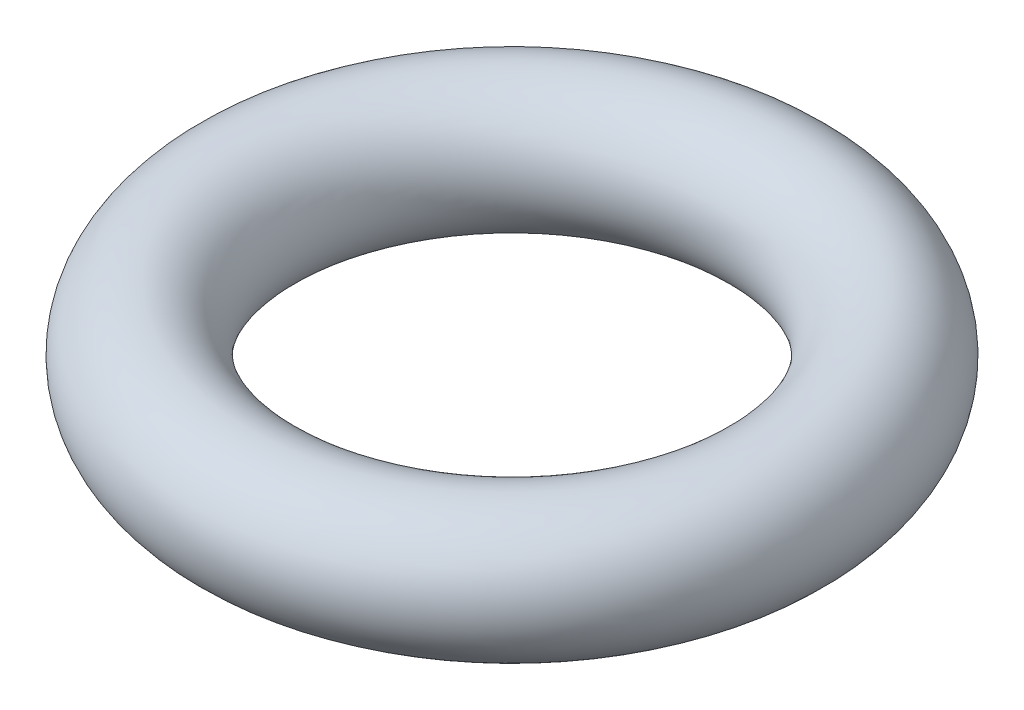
SolidWorks part; units mm, degrees
ref_plane "Front Plane" through (0, 0, 0) normal (0, 0, 1) x (1, 0, 0)
ref_plane "Top Plane" through (0, 0, 0) normal (0, 1, 0) x (1, 0, 0)
ref_plane "Right Plane" through (0, 0, 0) normal (1, 0, 0) x (0, 0, -1)
sketch "Sketch1" plane through (0, 0, 0) normal (0, 0, 1) x (1, 0, 0)
  line L0 (0, 0) -> (0, 24.0291) construction
  circle A0 centre (-20, 0) radius 5
  dimension "D2" = 10
  dimension "D3" = 20
revolve "Revolve1" add sketch "Sketch1" angle 360 about L0
equation "\"diameter\"=20"
equation "\"D3@Sketch1\"=\"diameter\""
equation "\"thickmess\"=10"
equation "\"D2@Sketch1\"=\"thickmess\""
